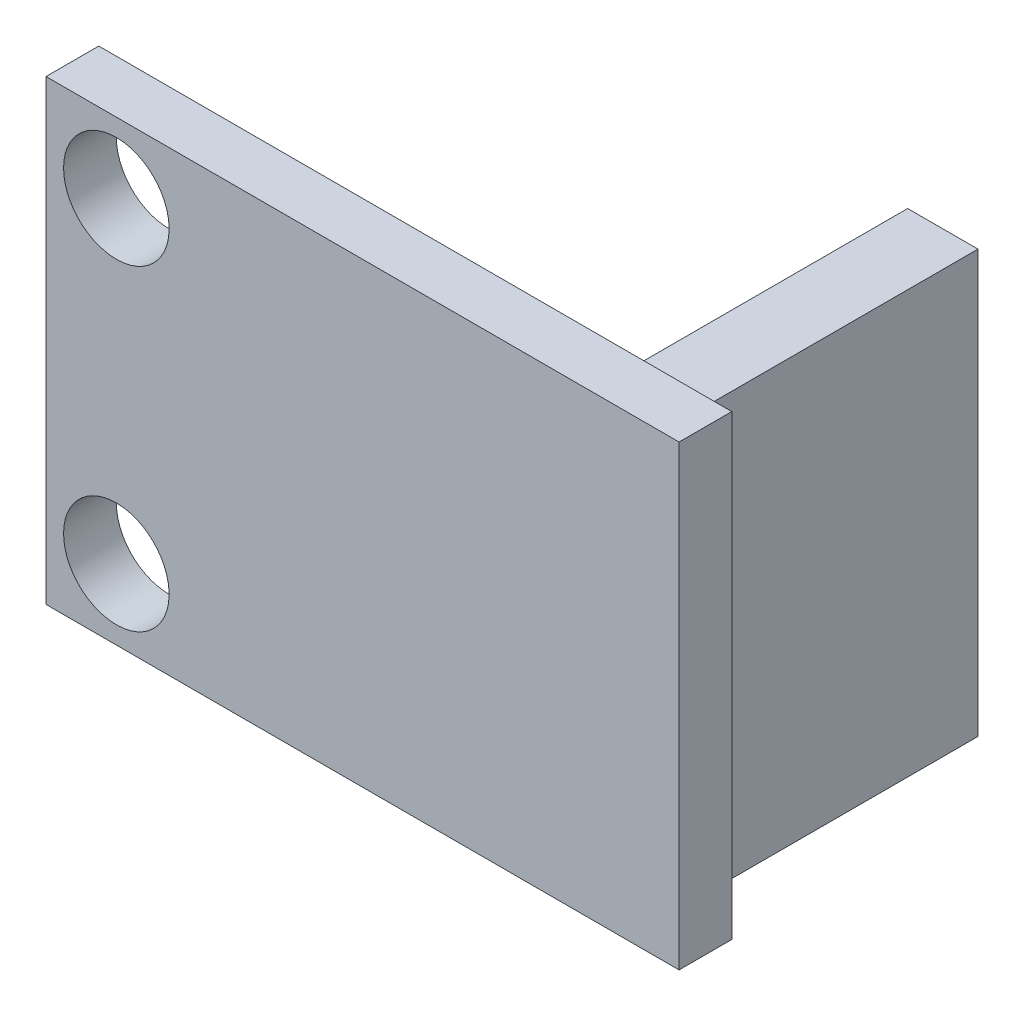
SolidWorks part; units mm, degrees
ref_plane "Plan de face" through (0, 0, 0) normal (0, 0, 1) x (1, 0, 0)
ref_plane "Plan de dessus" through (0, 0, 0) normal (0, 1, 0) x (1, 0, 0)
ref_plane "Plan de droite" through (0, 0, 0) normal (1, 0, 0) x (0, 0, -1)
sketch "Esquisse1" plane through (0, 0, 0) normal (0, 0, 1) x (1, 0, 0)
  line L1 (-9, -6.5) -> (9, -6.5)
  line L2 (-9, -6.5) -> (-9, 6.5)
  line L3 (-9, 6.5) -> (9, 6.5)
  line L4 (9, -6.5) -> (9, 6.5)
  line L5 (-9, -6.5) -> (9, 6.5) construction
  line L6 (-9, 6.5) -> (9, -6.5) construction
  point P0 (0, 0)
  dimension "D1" = 13
  dimension "D2" = 18
extrude "Boss.-Extru.1" add sketch "Esquisse1" along normal blind 1.5
sketch "Esquisse2" plane through (0, 0, 0) normal (0, 0, -1) x (-1, 0, 0)
  line L0 (9, 6.5) -> (9, -6.5) construction
  line L1 (-9, 6.5) -> (9, 6.5) construction
  circle A0 centre (7, 4.5) radius 1.5
  dimension "D1" = 3
  dimension "D2" = 2
  dimension "D3" = 2
extrude "Enlèv. mat.-Extru.1" cut sketch "Esquisse2" against normal up to next
mirror "Symétrie1" about plane through (0, 0, 0) normal (0, 1, 0) of "Enlèv. mat.-Extru.1"
sketch "Esquisse3" plane through (0, 0, 0) normal (0, 0, -1) x (-1, 0, 0)
  line L0 (-9, -6.5) -> (-9, 6.5) construction
  line L1 (-8, 6) -> (-6, 6)
  line L2 (-8, 6) -> (-8, -6)
  line L3 (-8, -6) -> (-6, -6)
  line L4 (-6, 6) -> (-6, -6)
  point P7 (-6, 0)
  dimension "D1" = 12
  dimension "D2" = 2
  dimension "D3" = 1
extrude "Boss.-Extru.2" add sketch "Esquisse3" along normal blind 8
sketch "Esquisse4" plane through (0, 0, 0) normal (0, 0, -1) x (-1, 0, 0)
  line L0 (9, 6.5) -> (9, -6.5) construction
  line L1 (-1, 1.5) -> (2, 1.5)
  line L2 (-1, 1.5) -> (-1, -1.5)
  line L3 (-1, -1.5) -> (2, -1.5)
  line L4 (2, 1.5) -> (2, -1.5)
  point P4 (-1, 0)
  dimension "D1" = 3
  dimension "D2" = 7
extrude "Boss.-Extru.3" add sketch "Esquisse4" along normal blind 1
